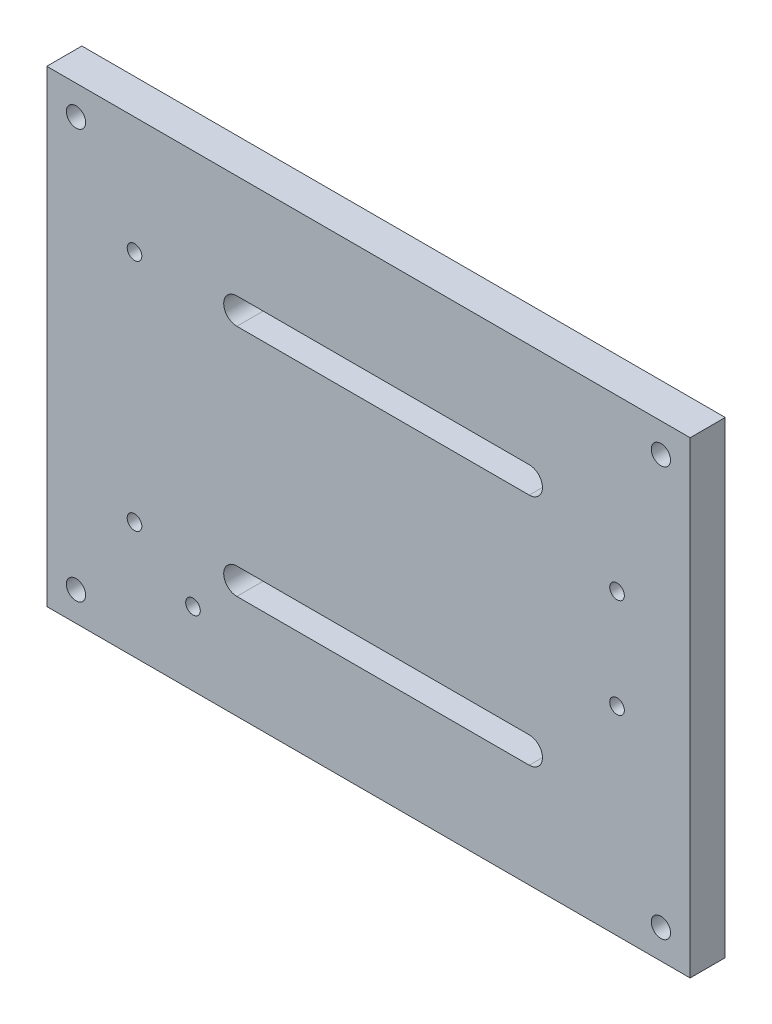
SolidWorks part; units mm, degrees
ref_plane "前视基准面" through (0, 0, 0) normal (0, 0, 1) x (1, 0, 0)
ref_plane "上视基准面" through (0, 0, 0) normal (0, 1, 0) x (1, 0, 0)
ref_plane "右视基准面" through (0, 0, 0) normal (1, 0, 0) x (0, 0, -1)
other "Configuration Table"
sketch "草图1" plane through (0, 0, 0) normal (0, 0, 1) x (1, 0, 0)
  line L1 (0, 0) -> (220, 0)
  line L2 (0, 0) -> (0, 160)
  line L3 (0, 160) -> (220, 160)
  line L4 (220, 0) -> (220, 160)
  line L5 (65, 44.5) -> (165, 44.5)
  line L6 (165, 35.5) -> (65, 35.5)
  line L7 (65, 124.5) -> (165, 124.5)
  line L8 (165, 115.5) -> (65, 115.5)
  circle A0 centre (10, 10) radius 3.3
  circle A1 centre (10, 150) radius 3.3
  circle A2 centre (210, 10) radius 3.3
  circle A3 centre (210, 150) radius 3.3
  circle A4 centre (30, 40) radius 2.5
  arc A5 (165, 44.5) -> (165, 35.5) centre (165, 40) cw
  arc A6 (65, 35.5) -> (65, 44.5) centre (65, 40) cw
  circle A7 centre (30, 120) radius 2.5
  arc A8 (165, 124.5) -> (165, 115.5) centre (165, 120) cw
  arc A9 (65, 115.5) -> (65, 124.5) centre (65, 120) cw
  circle A10 centre (50, 25) radius 2.5
  circle A11 centre (195, 68) radius 2.5
  circle A12 centre (195, 102) radius 2.5
extrude "Base_plate_220x160x12" add sketch "草图1" along normal blind 12
